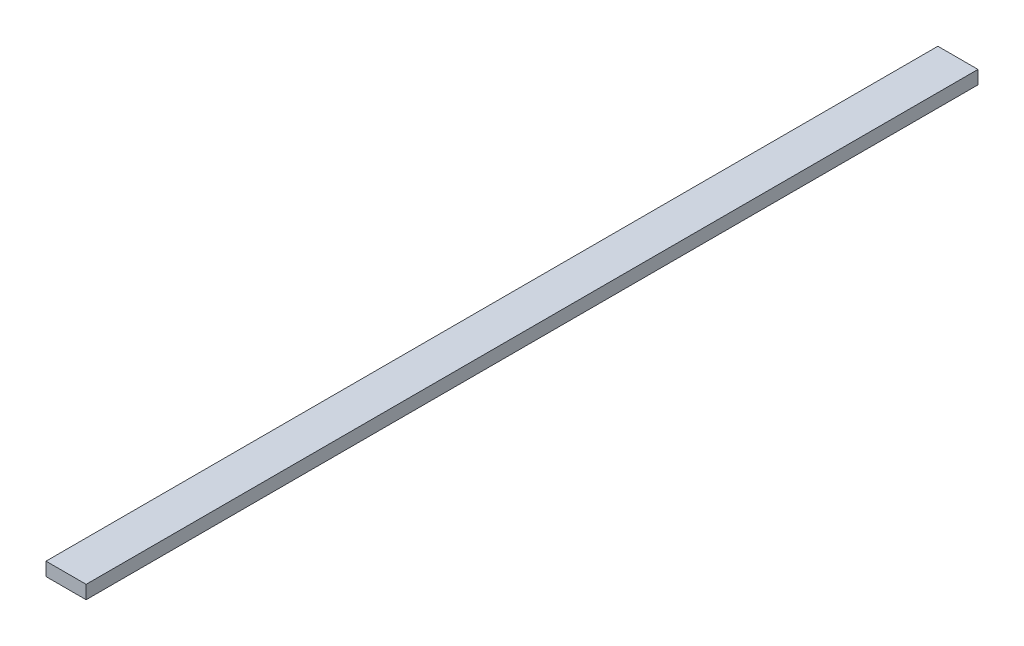
SolidWorks part; units mm, degrees
ref_plane "Front Plane" through (0, 0, 0) normal (0, 0, 1) x (1, 0, 0)
ref_plane "Top Plane" through (0, 0, 0) normal (0, 1, 0) x (1, 0, 0)
ref_plane "Right Plane" through (0, 0, 0) normal (1, 0, 0) x (0, 0, -1)
sketch "Sketch1" plane through (0, 0, 0) normal (0, 0, 1) x (1, 0, 0)
  line L1 (0, 0) -> (4.5, 0)
  line L2 (0, 0) -> (0, 1.5)
  line L3 (0, 1.5) -> (4.5, 1.5)
  line L4 (4.5, 0) -> (4.5, 1.5)
  dimension "D1" = 4.5
  dimension "D2" = 1.5
extrude "Boss-Extrude2" add sketch "Sketch1" along normal blind 100
